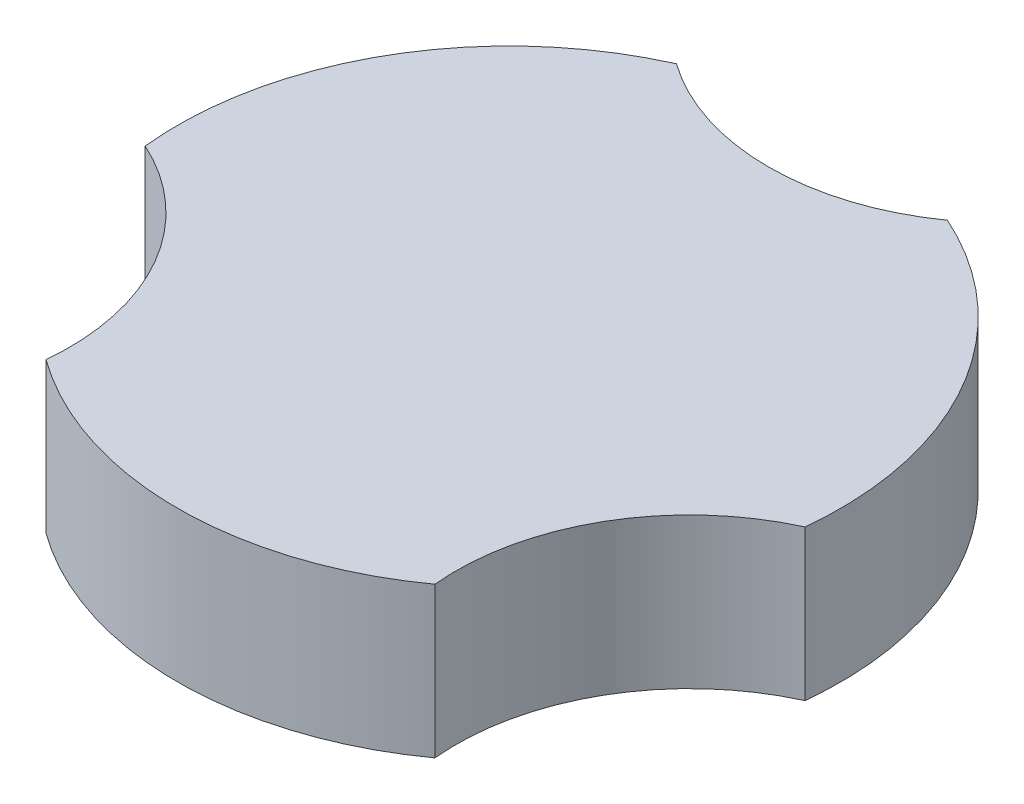
SolidWorks part; units mm, degrees
ref_plane "Front Plane" through (0, 0, 0) normal (0, 0, 1) x (1, 0, 0)
ref_plane "Top Plane" through (0, 0, 0) normal (0, 1, 0) x (1, 0, 0)
ref_plane "Right Plane" through (0, 0, 0) normal (1, 0, 0) x (0, 0, -1)
sketch "Sketch1" plane through (0, 0, 0) normal (0, 1, 0) x (1, 0, 0)
  circle A0 centre (0, 0) radius 14
  circle A1 centre (0, 0) radius 14 construction
  circle A2 centre (0, 20.8) radius 9.85
  circle A3 centre (18.0133, -10.4) radius 9.85
  circle A4 centre (-18.0133, -10.4) radius 9.85
  point P12 (0, 0)
  dimension "D1" = 28
  dimension "D2" = 28
  dimension "D3" = 19.7
  dimension "D4" = 20.8
  dimension "D5" = 3
extrude "Boss-Extrude1" add sketch "Sketch1" along normal blind 6.35 contours A4 A0 A3 A2
